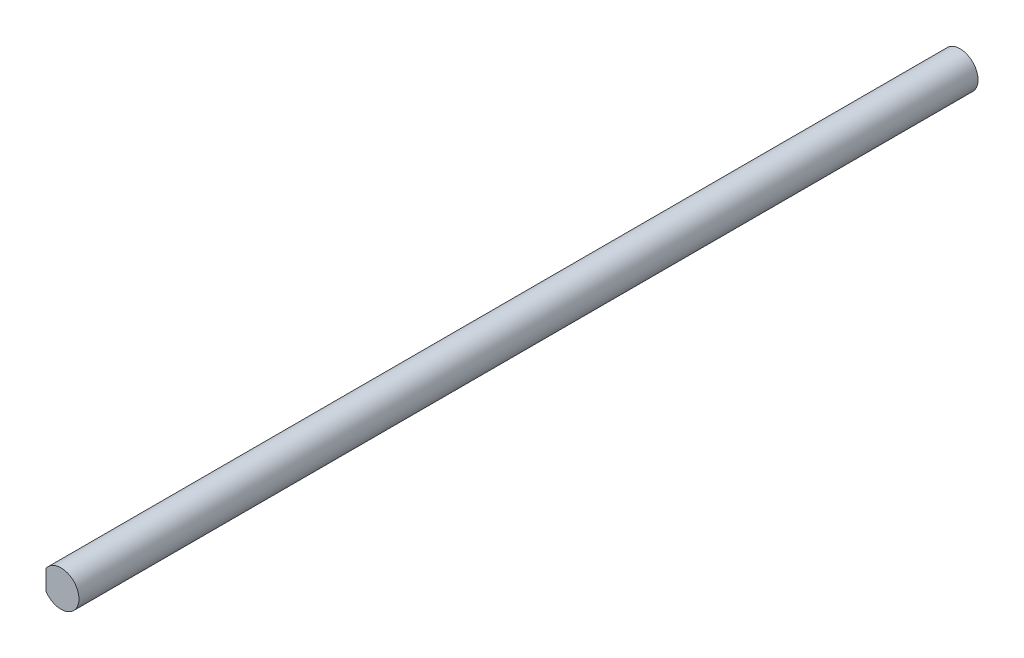
SolidWorks part; units mm, degrees
ref_plane "Front Plane" through (0, 0, 0) normal (0, 0, 1) x (1, 0, 0)
ref_plane "Top Plane" through (0, 0, 0) normal (0, 1, 0) x (1, 0, 0)
ref_plane "Right Plane" through (0, 0, 0) normal (1, 0, 0) x (0, 0, -1)
sketch "Sketch1" plane through (0, 0, 0) normal (0, 0, 1) x (1, 0, 0)
  line L0 (-2.5, 1.6583) -> (-2.5, -1.6583)
  line L1 (3, -3.1656) -> (3, 4.1153) construction
  arc A0 (-2.5, -1.6583) -> (-2.5, 1.6583) centre (0, 0) ccw
  dimension "D1" = 6
  dimension "D2" = 5.5
extrude "Boss-Extrude1" add sketch "Sketch1" along normal blind 150
